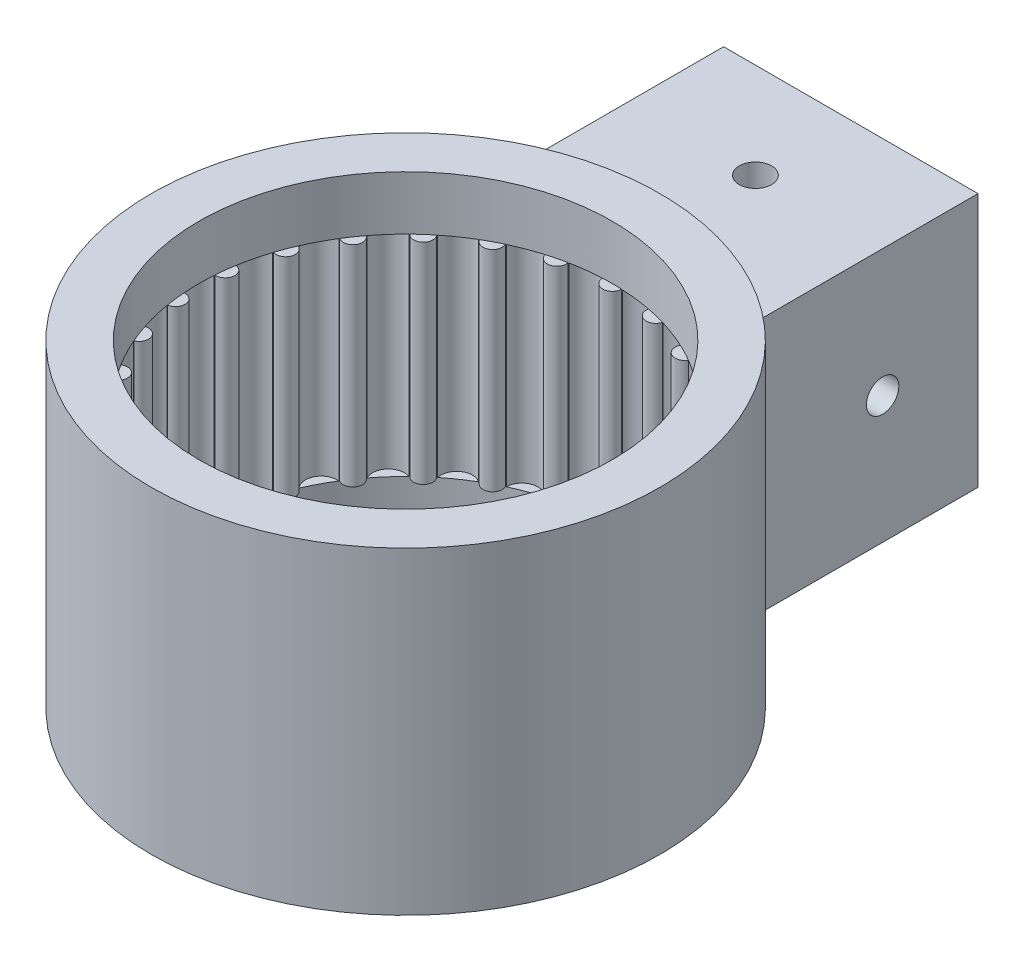
SolidWorks part; units mm, degrees
ref_plane "Front Plane" through (0, 0, 0) normal (0, 0, 1) x (1, 0, 0)
ref_plane "Top Plane" through (0, 0, 0) normal (0, 1, 0) x (1, 0, 0)
ref_plane "Right Plane" through (0, 0, 0) normal (1, 0, 0) x (0, 0, -1)
sketch "Sketch1" plane through (0, 0, 0) normal (0, 1, 0) x (1, 0, 0)
  circle A0 centre (0, 0) radius 32.5
  circle A1 centre (0, 0) radius 40
  dimension "D1" = 80
  dimension "D2" = 65
extrude "Boss-Extrude1" add sketch "Sketch1" along normal blind 50
ref_plane "Plane1" through (0, 41.5, 0) normal (0, 1, 0) x (1, 0, 0)
sketch "Sketch2" plane through (0, 41.5, 0) normal (0, 1, 0) x (1, 0, 0)
  circle A3 centre (0, 0) radius 32.5 construction
  circle A5 centre (0, 0) radius 32.5
  circle A7 centre (0, 32.5) radius 1.5
  circle A9 centre (7.7778, 31.5556) radius 1.5
  circle A11 centre (15.1035, 28.7773) radius 1.5
  circle A13 centre (21.5515, 24.3266) radius 1.5
  circle A15 centre (26.747, 18.4621) radius 1.5
  circle A17 centre (30.388, 11.5247) radius 1.5
  circle A19 centre (32.263, 3.9174) radius 1.5
  circle A21 centre (32.263, -3.9174) radius 1.5
  circle A23 centre (30.388, -11.5247) radius 1.5
  circle A25 centre (26.747, -18.4621) radius 1.5
  circle A27 centre (21.5515, -24.3266) radius 1.5
  circle A29 centre (15.1035, -28.7773) radius 1.5
  circle A31 centre (7.7778, -31.5556) radius 1.5
  circle A33 centre (0, -32.5) radius 1.5
  circle A35 centre (-7.7778, -31.5556) radius 1.5
  circle A37 centre (-15.1035, -28.7773) radius 1.5
  circle A39 centre (-21.5515, -24.3266) radius 1.5
  circle A41 centre (-26.747, -18.4621) radius 1.5
  circle A43 centre (-30.388, -11.5247) radius 1.5
  circle A45 centre (-32.263, -3.9174) radius 1.5
  circle A47 centre (-32.263, 3.9174) radius 1.5
  circle A49 centre (-30.388, 11.5247) radius 1.5
  circle A51 centre (-26.747, 18.4621) radius 1.5
  circle A53 centre (-21.5515, 24.3266) radius 1.5
  circle A75 centre (-15.1035, 28.7773) radius 1.5
  circle A76 centre (-7.7778, 31.5556) radius 1.5
  point P58 (0, 0)
  dimension "D1" = 3
extrude "Boss-Extrude3" add sketch "Sketch2" against normal blind 33 contours A5 A53 | A5 A75 | A5 A76 | A5 A51 | A5 A49 | A5 A7 | A5 A9 | A5 A11 | A5 A13 | A5 A15 | A5 A17 | A5 A19 | A5 A21 | A5 A23 | A5 A25 | A5 A27 | A5 A29 | A5 A31 | A5 A33 | A5 A35 | A5 A37 | A5 A39 | A5 A41 | A5 A43 | A5 A45 | A5 A47
sketch "Sketch3" plane through (0, 41.5, 0) normal (0, 1, 0) x (1, 0, 0)
  circle A0 centre (0, 0) radius 34
  circle A2 centre (0, 0) radius 32.5 construction
  circle A4 centre (0, 0) radius 32.5
  arc A5 (20.3229, 25.362) -> (16.5073, 27.9957) centre (17.9003, 25.9331) ccw
  arc A6 (25.8019, 19.7614) -> (22.7274, 23.2317) centre (23.5863, 20.8957) ccw
  arc A7 (29.7813, 13.0124) -> (27.6267, 17.1176) centre (27.9016, 14.6439) ccw
  arc A8 (32.03, 5.5072) -> (30.9205, 10.0087) centre (30.5954, 7.5411) ccw
  arc A9 (32.4172, -2.3181) -> (32.4172, 2.3181) centre (31.511, 0) ccw
  arc A10 (30.9205, -10.0087) -> (32.03, -5.5072) centre (30.5954, -7.5411) ccw
  arc A11 (27.6267, -17.1176) -> (29.7813, -13.0124) centre (27.9016, -14.6439) ccw
  arc A12 (22.7274, -23.2317) -> (25.8019, -19.7614) centre (23.5863, -20.8957) ccw
  arc A13 (16.5073, -27.9957) -> (20.3229, -25.362) centre (17.9003, -25.9331) ccw
  arc A14 (9.3278, -31.1327) -> (13.6628, -29.4886) centre (11.174, -29.4633) ccw
  arc A15 (1.6062, -32.4603) -> (6.2087, -31.9014) centre (3.7982, -31.2813) ccw
  arc A16 (-6.2087, -31.9014) -> (-1.6062, -32.4603) centre (-3.7982, -31.2813) ccw
  arc A17 (-13.6628, -29.4886) -> (-9.3278, -31.1327) centre (-11.174, -29.4633) ccw
  arc A18 (-20.3229, -25.362) -> (-16.5073, -27.9957) centre (-17.9003, -25.9331) ccw
  arc A19 (-25.8019, -19.7614) -> (-22.7274, -23.2317) centre (-23.5863, -20.8957) ccw
  arc A20 (-29.7813, -13.0124) -> (-27.6267, -17.1176) centre (-27.9016, -14.6439) ccw
  arc A21 (-32.03, -5.5072) -> (-30.9205, -10.0087) centre (-30.5954, -7.5411) ccw
  arc A22 (-32.4172, 2.3181) -> (-32.4172, -2.3181) centre (-31.511, 0) ccw
  arc A23 (-30.9205, 10.0087) -> (-32.03, 5.5072) centre (-30.5954, 7.5411) ccw
  arc A24 (-27.6267, 17.1176) -> (-29.7813, 13.0124) centre (-27.9016, 14.6439) ccw
  arc A25 (-22.7274, 23.2317) -> (-25.8019, 19.7614) centre (-23.5863, 20.8957) ccw
  arc A26 (-16.5073, 27.9957) -> (-20.3229, 25.362) centre (-17.9003, 25.9331) ccw
  arc A27 (-9.3278, 31.1327) -> (-13.6628, 29.4886) centre (-11.174, 29.4633) ccw
  arc A28 (-1.6062, 32.4603) -> (-6.2087, 31.9014) centre (-3.7982, 31.2813) ccw
  arc A29 (6.2087, 31.9014) -> (1.6062, 32.4603) centre (3.7982, 31.2813) ccw
  arc A30 (13.6628, 29.4886) -> (9.3278, 31.1327) centre (11.174, 29.4633) ccw
  point P86 (0, 0)
  dimension "D1" = 68
extrude "Cut-Extrude1" cut sketch "Sketch3" against normal blind 33 contours A4 A5 | A4 A30 | A4 A29 | A4 A28 | A4 A27 | A4 A26 | A4 A24 | A4 A23 | A4 A22 | A4 A21 | A4 A20 | A4 A6 | A4 A7 | A4 A8 | A4 A9 | A4 A10 | A11 A4 | A12 A4 | A13 A4 | A14 A4 | A15 A4 | A4 A16 | A4 A17 | A4 A18 | A4 A19 | A4 A25
ref_plane "Plane2" through (0, 0, -70) normal (0, 0, 1) x (1, 0, 0)
sketch "Sketch4" plane through (0, 0, -70) normal (0, 0, 1) x (1, 0, 0)
  line L0 (0, 0) -> (0, 25) construction
  line L2 (20, 45) -> (-20, 45)
  line L3 (20, 45) -> (20, 5)
  line L4 (20, 5) -> (-20, 5)
  line L5 (-20, 45) -> (-20, 5)
  line L6 (20, 45) -> (-20, 5) construction
  line L7 (20, 5) -> (-20, 45) construction
  line L8 (-10.05, 14.95) -> (10.05, 14.95)
  line L9 (-10.05, 14.95) -> (-10.05, 35.05)
  line L10 (-10.05, 35.05) -> (10.05, 35.05)
  line L11 (10.05, 14.95) -> (10.05, 35.05)
  line L12 (-10.05, 14.95) -> (10.05, 35.05) construction
  line L13 (-10.05, 35.05) -> (10.05, 14.95) construction
  dimension "D1" = 25
  dimension "D2" = 40
  dimension "D3" = 40
  dimension "D4" = 20.1
  dimension "D5" = 20.1
extrude "Boss-Extrude4" add sketch "Sketch4" along normal up to surface (35.359 mm away)
sketch "Sketch5" plane through (0, 45, 0) normal (0, 1, 0) x (1, 0, 0)
  line L0 (0, 0) -> (0, 55) construction
  circle A0 centre (0, 55) radius 2.55
  dimension "D2" = 5.1
  dimension "D1" = 55
extrude "Cut-Extrude2" cut sketch "Sketch5" against normal blind 40
sketch "Sketch6" plane through (-20, 0, 0) normal (-1, 0, 0) x (0, 0, 1)
  line L0 (0, 0) -> (0, 25) construction
  line L1 (0, 25) -> (-55, 25) construction
  circle A0 centre (-55, 25) radius 2.55
  dimension "D3" = 5.1
  dimension "D1" = 25
  dimension "D2" = 55
extrude "Cut-Extrude3" cut sketch "Sketch6" against normal blind 40
